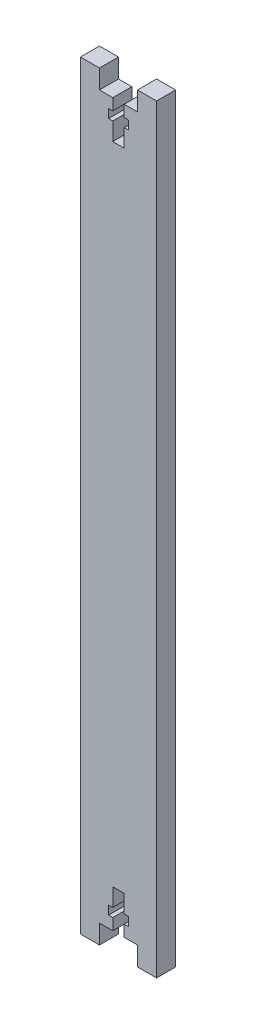
SolidWorks part; units mm, degrees
ref_plane "Front Plane" through (0, 0, 0) normal (0, 0, 1) x (1, 0, 0)
ref_plane "Top Plane" through (0, 0, 0) normal (0, 1, 0) x (1, 0, 0)
ref_plane "Right Plane" through (0, 0, 0) normal (1, 0, 0) x (0, 0, -1)
sketch "Sketch1" plane through (0, 0, 0) normal (0, 0, 1) x (1, 0, 0)
  line L0 (0, 194.5) -> (0, 5)
  line L5 (-20, 194.5) -> (-20, 5)
  line L6 (-10, 5) -> (-10, 16.2208) construction
  line L7 (-11.5, 5) -> (-15, 5)
  line L8 (-15, 0) -> (-20, 0)
  line L9 (-20, 0) -> (-20, 5)
  line L10 (-15, 0) -> (-15, 5)
  line L11 (-8.5, 5) -> (-5, 5)
  line L12 (-5, 5) -> (-5, 0)
  line L13 (-5, 0) -> (0, 0)
  line L14 (0, 0) -> (0, 5)
  line L15 (-10, 194.5) -> (-10, 183.2792) construction
  line L16 (-8.5, 194.5) -> (-5, 194.5)
  line L17 (-5, 199.5) -> (0, 199.5)
  line L18 (0, 199.5) -> (0, 194.5)
  line L19 (-5, 199.5) -> (-5, 194.5)
  line L20 (-11.5, 194.5) -> (-15, 194.5)
  line L21 (-15, 194.5) -> (-15, 199.5)
  line L22 (-15, 199.5) -> (-20, 199.5)
  line L23 (-20, 199.5) -> (-20, 194.5)
  line L24 (-8.5, 194.5) -> (-11.5, 194.5) construction
  line L25 (-11.5, 194.5) -> (-11.5, 191.5)
  line L26 (-11.5, 189.2) -> (-12.6, 189.2)
  line L27 (-7.4, 191.5) -> (-7.4, 189.2)
  line L28 (-12.6, 191.5) -> (-11.5, 191.5)
  line L29 (-11.5, 189.2) -> (-11.5, 184.5)
  line L30 (-11.5, 184.5) -> (-8.5, 184.5)
  line L31 (-8.5, 184.5) -> (-8.5, 189.2)
  line L32 (-8.5, 191.5) -> (-7.4, 191.5)
  line L33 (-12.6, 189.2) -> (-12.6, 191.5)
  line L34 (-7.4, 189.2) -> (-8.5, 189.2)
  line L35 (-8.5, 191.5) -> (-8.5, 194.5)
  line L36 (-10, 184.5) -> (-10, 194.5) construction
  line L37 (-11.5, 5) -> (-8.5, 5) construction
  line L38 (-8.5, 5) -> (-8.5, 8)
  line L39 (-8.5, 10.3) -> (-7.4, 10.3)
  line L40 (-12.6, 8) -> (-12.6, 10.3)
  line L41 (-7.4, 8) -> (-8.5, 8)
  line L42 (-8.5, 10.3) -> (-8.5, 15)
  line L43 (-8.5, 15) -> (-11.5, 15)
  line L44 (-11.5, 15) -> (-11.5, 10.3)
  line L45 (-11.5, 8) -> (-12.6, 8)
  line L46 (-7.4, 10.3) -> (-7.4, 8)
  line L47 (-12.6, 10.3) -> (-11.5, 10.3)
  line L48 (-11.5, 8) -> (-11.5, 5)
  line L49 (-10, 15) -> (-10, 5) construction
  point P4 (-17.5, 0)
  dimension "D1" = 10
  dimension "D2" = 5
  dimension "D3" = 5
  dimension "D4" = 10
  dimension "D5" = 5
  dimension "D6" = 5
  dimension "D7" = 5.2
  dimension "D8" = 3
  dimension "D9" = 2.3
  dimension "D10" = 3
  dimension "D11" = 10
  dimension "D12" = 5.2
  dimension "D13" = 3
  dimension "D14" = 2.3
  dimension "D15" = 3
  dimension "D16" = 10
  dimension "D17" = 199.5
extrude "Boss-Extrude1" add sketch "Sketch1" along normal blind 5
sketch "Sketch2" plane through (0, 0, 5) normal (0, 0, 1) x (1, 0, 0)
  line L0 (-9.9476, 274.152) -> (-9.9476, -26.6804) construction
  line L1 (0, 0) -> (0, 199.5) construction
  dimension "D1" = 9.9476
